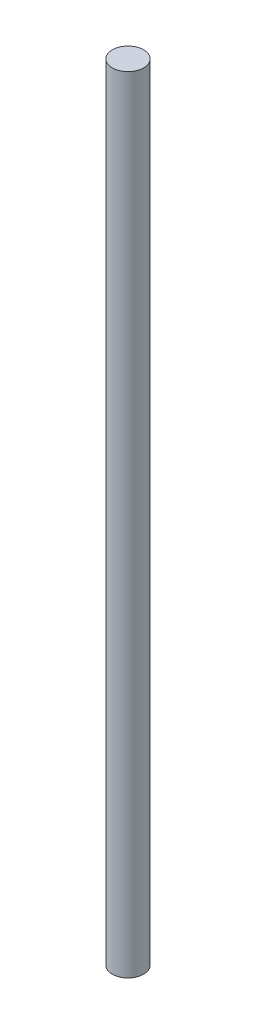
SolidWorks part; units mm, degrees
ref_plane "Plan de face" through (0, 0, 0) normal (0, 0, 1) x (1, 0, 0)
ref_plane "Plan de dessus" through (0, 0, 0) normal (0, 1, 0) x (1, 0, 0)
ref_plane "Plan de droite" through (0, 0, 0) normal (1, 0, 0) x (0, 0, -1)
sketch "Esquisse1" plane through (0, 0, 0) normal (0, 1, 0) x (1, 0, 0)
  circle A0 centre (0, 0) radius 3
  dimension "D1" = 6
extrude "Boss.-Extru.1" add sketch "Esquisse1" along normal blind 150
